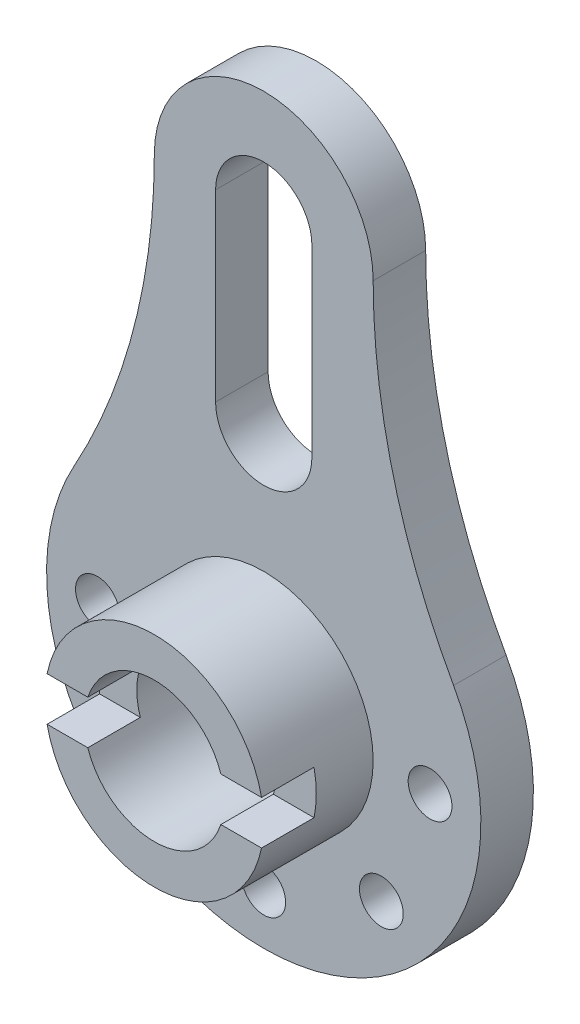
SolidWorks part; units mm, degrees
ref_plane "前基準面" through (0, 0, 0) normal (0, 0, 1) x (1, 0, 0)
ref_plane "上基準面" through (0, 0, 0) normal (0, 1, 0) x (1, 0, 0)
ref_plane "右基準面" through (0, 0, 0) normal (1, 0, 0) x (0, 0, -1)
sketch "草圖1" plane through (0, 0, 0) normal (0, 0, 1) x (1, 0, 0)
  line L0 (-11, 95) -> (-11, 53)
  line L1 (11, 95) -> (11, 53)
  line L2 (-11, 74) -> (62.5665, 74) construction
  line L3 (-36.9324, 95) -> (50.0179, 95) construction
  line L4 (0, 95) -> (0, 15.2388) construction
  arc A0 (25, 95) -> (-25, 95) centre (0, 95) ccw
  arc A1 (11, 95) -> (-11, 95) centre (0, 95) ccw
  arc A2 (11, 53) -> (-11, 53) centre (0, 53) cw
  arc A3 (-43.373, 24.0961) -> (43.373, 24.0961) centre (0, 0) ccw
  arc A4 (-43.373, 24.0961) -> (-25, 95) centre (-171, 95) ccw
  arc A5 (43.373, 24.0961) -> (25, 95) centre (171, 95) cw
  point P12 (11, 74)
  dimension "D2" = 25
  dimension "D3" = 146
  dimension "D1" = 22
  dimension "D4" = 42
  dimension "D5" = 95
extrude "填料-伸長1" add sketch "草圖1" along normal blind 12
sketch "草圖2" plane through (0, 0, 12) normal (0, 0, 1) x (1, 0, 0)
  line L0 (0, 0) -> (59.9598, 0) construction
  line L1 (59.9598, 0) -> (-77.8445, 0) construction
  line L2 (0, 0) -> (0, 53) construction
  circle A0 centre (38, 0) radius 5
  circle A1 centre (-38, 0) radius 5
  circle A2 centre (26.8701, -26.8701) radius 5
  circle A3 centre (0, -38) radius 5
  circle A4 centre (-26.8701, -26.8701) radius 5
  circle A5 centre (-38, 0) radius 5
  point P20 (0, 0)
  dimension "D2" = 10
  dimension "D3" = 38
  dimension "D4" = 38
  dimension "D1" = 5
extrude "除料-伸長1" cut sketch "草圖2" against normal through all contours A0 | A1 | A4 | A3 | A2
sketch "草圖3" plane through (0, 0, 12) normal (0, 0, 1) x (1, 0, 0)
  circle A0 centre (0, 0) radius 25
  dimension "D1" = 50
extrude "填料-伸長2" add sketch "草圖3" along normal blind 25
sketch "草圖4" plane through (0, 0, 37) normal (0, 0, 1) x (1, 0, 0)
  circle A0 centre (0, 0) radius 16
  dimension "D1" = 32
extrude "除料-伸長2" cut sketch "草圖4" against normal through all
sketch "草圖5" plane through (0, 0, 37) normal (0, 0, 1) x (1, 0, 0)
  line L0 (-24.4949, 5) -> (-15.1987, 5)
  line L1 (-15.1987, -5) -> (-24.4949, -5)
  line L2 (28.2926, 0) -> (-28.2926, 0) construction
  line L3 (0, 0) -> (0, 22.7672) construction
  line L4 (15.1987, -5) -> (24.4949, -5)
  line L5 (24.4949, 5) -> (15.1987, 5)
  circle A0 centre (0, 0) radius 25 construction
  circle A1 centre (0, 0) radius 16 construction
  circle A2 centre (0, 0) radius 25 construction
  arc A3 (-24.4949, 5) -> (-24.4949, -5) centre (0, 0) ccw
  arc A4 (-15.1987, 5) -> (-15.1987, -5) centre (0, 0) ccw
  arc A5 (15.1987, 5) -> (15.1987, -5) centre (0, 0) cw
  arc A6 (24.4949, 5) -> (24.4949, -5) centre (0, 0) cw
  dimension "D1" = 10
extrude "除料-伸長3" cut sketch "草圖5" against normal blind 12
